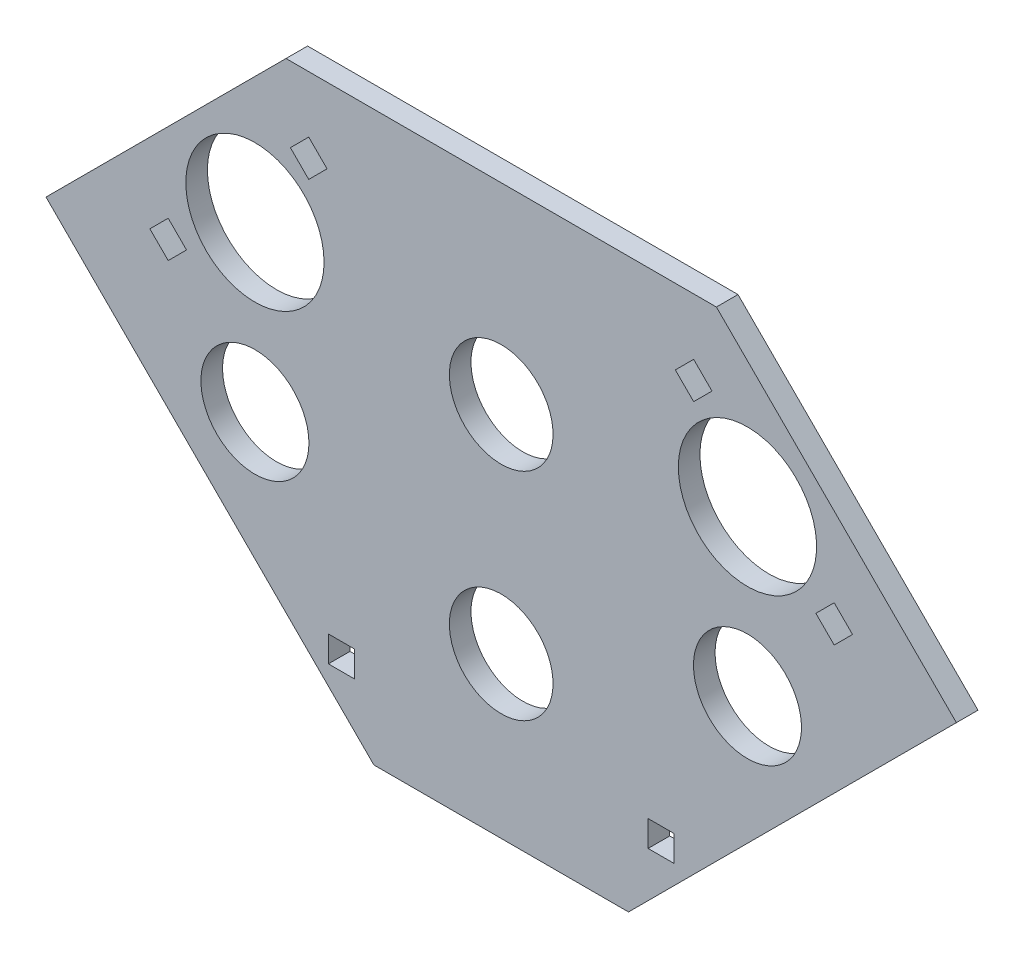
SolidWorks part; units mm, degrees
material "ABS"
ref_plane "Front Plane" through (0, 0, 0) normal (0, 0, 1) x (1, 0, 0)
ref_plane "Top Plane" through (0, 0, 0) normal (0, 1, 0) x (1, 0, 0)
ref_plane "Right Plane" through (0, 0, 0) normal (1, 0, 0) x (0, 0, -1)
sketch "Sketch3" plane through (0, 0, 0) normal (0, 0, 1) x (1, 0, 0)
  line L8 (0, 0) -> (136.4293, 136.4293) construction
  line L9 (0, 0) -> (0, 136.4293) construction
  line L10 (0, 0) -> (-136.4293, 136.4293) construction
  line L20 (-15.2843, -13) -> (15.2843, -13) construction
  line L23 (-15.2843, -13) -> (-77.7817, 49.4975) construction
  line L25 (15.2843, -13) -> (77.7817, 49.4975) construction
  line L27 (-77.7817, 49.4975) -> (-49.4975, 77.7817)
  line L29 (49.4975, 77.7817) -> (77.7817, 49.4975)
  line L32 (-15.2843, -13) -> (15.2843, -13) construction
  line L34 (-27.4975, -22) -> (27.4975, -22)
  line L36 (-27.4975, -22) -> (-88.3883, 38.8909)
  line L37 (-88.3883, 38.8909) -> (-77.7817, 49.4975)
  line L42 (-49.4975, 77.7817) -> (-40.0115, 68.2957) construction
  line L47 (27.4975, -22) -> (88.3883, 38.8909)
  line L48 (88.3883, 38.8909) -> (77.7817, 49.4975)
  line L49 (0, 0) -> (0, -22) construction
  line L50 (-49.4975, 77.7817) -> (-43.8406, 83.4386)
  line L51 (-43.8406, 83.4386) -> (43.8406, 83.4386)
  line L52 (43.8406, 83.4386) -> (49.4975, 77.7817)
  line L53 (49.4975, 77.7817) -> (23.1501, 51.4344) construction
  line L54 (-43.8406, 83.4386) -> (-20.3266, 59.9246) construction
  line L55 (43.8406, 83.4386) -> (35.6049, 75.2028) construction
  line L56 (-81.3173, 44.5477) -> (-77.0746, 48.7904)
  line L57 (-77.0746, 48.7904) -> (-72.832, 44.5477)
  line L58 (-72.832, 44.5477) -> (-77.0746, 40.3051)
  line L59 (-77.0746, 40.3051) -> (-81.3173, 44.5477)
  line L60 (-48.7904, 77.0746) -> (-44.5477, 81.3173)
  line L61 (-44.5477, 81.3173) -> (-40.3051, 77.0746)
  line L62 (-40.3051, 77.0746) -> (-44.5477, 72.832)
  line L63 (-44.5477, 72.832) -> (-48.7904, 77.0746)
  line L64 (40.3051, 77.0746) -> (44.5477, 72.832)
  line L71 (44.5477, 72.832) -> (48.7904, 77.0746)
  line L72 (48.7904, 77.0746) -> (44.5477, 81.3173)
  line L73 (44.5477, 81.3173) -> (40.3051, 77.0746)
  line L74 (72.832, 44.5477) -> (77.0746, 40.3051)
  line L75 (77.0746, 40.3051) -> (81.3173, 44.5477)
  line L76 (81.3173, 44.5477) -> (77.0746, 48.7904)
  line L77 (77.0746, 48.7904) -> (72.832, 44.5477)
  line L82 (0, 0) -> (0, 50) construction
  circle A0 centre (0, 0) radius 12
  circle A1 centre (0, 50) radius 12
  point P7 (63.6396, 63.6396)
  point P15 (-63.6396, 63.6396)
  dimension "crankshaftBearingOD" = 24
  dimension "D22" = 24
  dimension "D8" = 45
  dimension "D10" = 45
  dimension "D2" = 90
  dimension "D3" = 90
  dimension "D4" = 40
  dimension "D5" = 40
  dimension "D6" = 13
  dimension "D7" = 22
  dimension "D9" = 8
  dimension "D11" = 15
  dimension "D15" = 1
  dimension "D16" = 6
  dimension "D18" = 1
  dimension "D19" = 6
  dimension "D12" = 176.7767
  dimension "D13" = 105.4386
  dimension "D17" = 50
extrude "Boss-Extrude1" add sketch "Sketch3" along normal blind 5
sketch "Sketch5" plane through (0, 0, 5) normal (0, 0, 1) x (1, 0, 0)
  line L24 (-43.8406, 83.4386) -> (-88.3883, 38.8909)
  line L25 (-88.3883, 38.8909) -> (-27.4975, -22)
  line L26 (-27.4975, -22) -> (27.4975, -22)
  line L27 (27.4975, -22) -> (88.3883, 38.8909)
  line L28 (88.3883, 38.8909) -> (43.8406, 83.4386)
  line L29 (43.8406, 83.4386) -> (-43.8406, 83.4386)
  line L30 (-43.8406, 83.4386) -> (-88.3883, 38.8909)
  line L31 (-88.3883, 38.8909) -> (-27.4975, -22)
  line L32 (-27.4975, -22) -> (27.4975, -22)
  line L33 (27.4975, -22) -> (88.3883, 38.8909)
  line L34 (88.3883, 38.8909) -> (43.8406, 83.4386)
  line L35 (43.8406, 83.4386) -> (-43.8406, 83.4386)
  line L36 (-105.3589, 38.8909) -> (-49.8112, 94.4386)
  line L37 (-49.8112, 94.4386) -> (49.8112, 94.4386)
  line L38 (49.8112, 94.4386) -> (105.3589, 38.8909)
  line L39 (105.3589, 38.8909) -> (29.468, -37)
  line L40 (29.468, -37) -> (-29.468, -37)
  line L41 (-29.468, -37) -> (-105.3589, 38.8909)
  dimension "D2" = 11
  dimension "D3" = 15
  dimension "D4" = 12
  dimension "D5" = 12
  dimension "D6" = 12
  dimension "D7" = 12
  dimension "D1" = 0
extrude "Boss-Extrude2" add sketch "Sketch5" against normal up to surface (5 mm away) up to face at (-44.5477, 77.0746, 0)
sketch "Sketch6" plane through (0, 0, 5) normal (0, 0, 1) x (1, 0, 0)
  line L0 (-42.468, -24) -> (42.468, -24) construction
  line L1 (-40, -22) -> (-34, -22)
  line L2 (-40, -22) -> (-40, -16)
  line L3 (-40, -16) -> (-34, -16)
  line L4 (-34, -22) -> (-34, -16)
  line L5 (-40, -22) -> (-34, -16) construction
  line L6 (-40, -16) -> (-34, -22) construction
  line L7 (34, -22) -> (40, -22)
  line L8 (34, -22) -> (34, -16)
  line L9 (34, -16) -> (40, -16)
  line L10 (40, -22) -> (40, -16)
  line L11 (34, -22) -> (40, -16) construction
  line L12 (34, -16) -> (40, -22) construction
  line L13 (-105.3589, 38.8909) -> (-29.468, -37) construction
  line L14 (29.468, -37) -> (105.3589, 38.8909) construction
  line L15 (0, 50) -> (0, 0) construction
  line L16 (-48.7904, 77.0746) -> (-77.0746, 48.7904) construction
  line L17 (-77.0746, 48.7904) -> (-62.9325, 62.9325) construction
  line L18 (-62.9325, 62.9325) -> (0, 0) construction
  circle A0 centre (-57, 58) radius 16
  circle A1 centre (-57, 20) radius 12.5
  circle A2 centre (0, 50) radius 40 construction
  circle A3 centre (0, 0) radius 40 construction
  circle A4 centre (57, 20) radius 12.5
  circle A5 centre (57, 58) radius 16
  point P0 (-37, -19)
  point P5 (37, -19)
  dimension "D7" = 25
  dimension "D8" = 57
  dimension "D12" = 80
  dimension "D13" = 32
  dimension "D1" = 6
  dimension "D2" = 24
  dimension "D3" = 2
  dimension "D4" = 2
  dimension "D5" = 37
  dimension "D6" = 37
  dimension "D9" = 8
  dimension "D10" = 57
  dimension "D11" = 20
extrude "Cut-Extrude1" cut sketch "Sketch6" against normal up to surface (5 mm away) up to face at (-44.5477, 77.0746, 0)
sketch "Sketch7" plane through (0, 0, 0) normal (0, 0, 1) x (1, 0, 0)
  line L0 (0, 0) -> (21.1195, 0) construction
  line L1 (21.1195, 0) -> (21.1195, 11.4) construction
  circle A0 centre (21.1195, 11.4) radius 7.5
  point P4 (21.1195, 11.4)
  dimension "D3" = 15
  dimension "D1" = 11.4
  dimension "D2" = 21.1195
extrude "Boss-Extrude3" add sketch "Sketch7" against normal blind 10
sketch "Sketch8" plane through (0, 0, 0) normal (0, 0, -1) x (-1, 0, 0)
  circle A0 centre (-21.1195, 11.4) radius 7.5 construction
  circle A1 centre (-21.1195, 11.4) radius 7.5
  circle A2 centre (-21.1195, 11.4) radius 9.5
  dimension "D1" = 2
extrude "Boss-Extrude4" add sketch "Sketch8" along normal blind 2.5
equation "\"crankshaftBearingOD@Sketch3\"=24.00mm"
